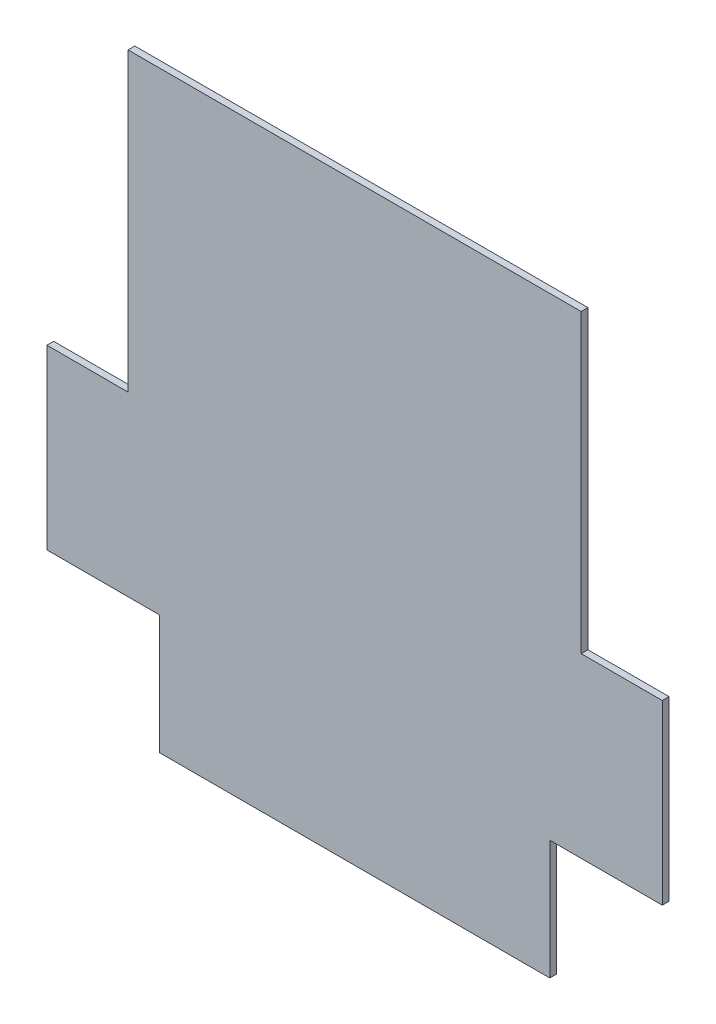
SolidWorks part; units mm, degrees
ref_plane "Front Plane" through (0, 0, 0) normal (0, 0, 1) x (1, 0, 0)
ref_plane "Top Plane" through (0, 0, 0) normal (0, 1, 0) x (1, 0, 0)
ref_plane "Right Plane" through (0, 0, 0) normal (1, 0, 0) x (0, 0, -1)
sketch "Sketch1" plane through (0, 0, 0) normal (0, 0, 1) x (1, 0, 0)
  line L1 (0, 0) -> (273.4, 0)
  line L2 (0, 0) -> (0, -263.4)
  line L3 (0, -263.4) -> (273.4, -263.4)
  line L4 (273.4, 0) -> (273.4, -263.4)
  dimension "D1" = 273.4
  dimension "D2" = 263.4
extrude "Boss-Extrude1" add sketch "Sketch1" along normal blind 3
sketch "Sketch2" plane through (0, 0, 3) normal (0, 0, 1) x (1, 0, 0)
  line L1 (0, 0) -> (36.05, 0)
  line L2 (0, 0) -> (0, -131.64)
  line L3 (0, -131.64) -> (36.05, -131.64)
  line L4 (36.05, 0) -> (36.05, -131.64)
  line L5 (0, -263.4) -> (50, -263.4)
  line L6 (0, -263.4) -> (0, -210.4)
  line L7 (0, -210.4) -> (50, -210.4)
  line L8 (50, -263.4) -> (50, -210.4)
  line L9 (273.4, 0) -> (237.35, 0)
  line L10 (273.4, 0) -> (273.4, -131.64)
  line L11 (273.4, -131.64) -> (237.35, -131.64)
  line L12 (237.35, 0) -> (237.35, -131.64)
  line L13 (273.4, -263.4) -> (223.4, -263.4)
  line L14 (273.4, -263.4) -> (273.4, -210.4)
  line L15 (273.4, -210.4) -> (223.4, -210.4)
  line L16 (223.4, -263.4) -> (223.4, -210.4)
  dimension "D1" = 36.05
  dimension "D2" = 131.64
  dimension "D3" = 50
  dimension "D4" = 53
  dimension "D5" = 36.05
  dimension "D6" = 131.64
  dimension "D7" = 50
  dimension "D8" = 53
extrude "Cut-Extrude1" cut sketch "Sketch2" against normal through all
